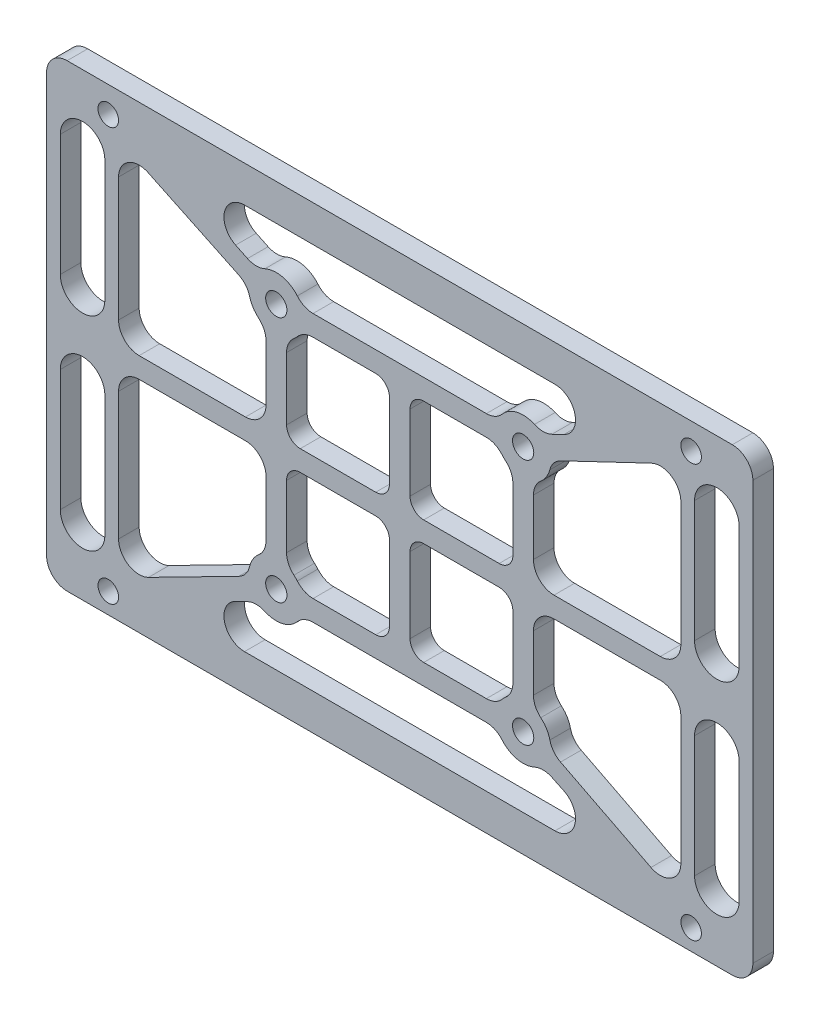
SolidWorks part; units mm, degrees
material "Thornel Mat VMA"
ref_plane "前视基准面" through (0, 0, 0) normal (0, 0, 1) x (1, 0, 0)
ref_plane "上视基准面" through (0, 0, 0) normal (0, 1, 0) x (1, 0, 0)
ref_plane "右视基准面" through (0, 0, 0) normal (1, 0, 0) x (0, 0, -1)
sketch "草图1" plane through (0, 0, 0) normal (0, 0, 1) x (1, 0, 0)
  line L1 (51.5, -33.5) -> (-51.5, -33.5)
  line L2 (51.5, -33.5) -> (51.5, 33.5)
  line L3 (51.5, 33.5) -> (-51.5, 33.5)
  line L4 (-51.5, -33.5) -> (-51.5, 33.5)
  line L5 (51.5, -33.5) -> (-51.5, 33.5) construction
  line L6 (51.5, 33.5) -> (-51.5, -33.5) construction
  point P0 (0, 0)
  dimension "D1" = 67
  dimension "D2" = 103
extrude "凸台-拉伸1" add sketch "草图1" along normal blind 3
sketch "草图2" plane through (0, 0, 3) normal (0, 0, 1) x (1, 0, 0)
  line L0 (0, 0) -> (-50000, 0) construction
  line L1 (0, 0) -> (0, 50000) construction
  circle A0 centre (-18, 18) radius 1.55
  circle A1 centre (18, 18) radius 1.55
  circle A2 centre (18, -18) radius 1.55
  circle A3 centre (-18, -18) radius 1.55
  circle A4 centre (42.5, 29.7) radius 1.5 construction
  circle A5 centre (42.5, -30.5) radius 1.5 construction
  circle A6 centre (-42.5, -30.5) radius 1.5 construction
  circle A7 centre (-42.5, 29.7) radius 1.5 construction
  circle A8 centre (42.5, 29.7) radius 1.5
  circle A9 centre (42.5, -30.5) radius 1.5
  circle A10 centre (-42.5, -30.5) radius 1.5
  circle A11 centre (-42.5, 29.7) radius 1.5
  dimension "D1" = 3.1
  dimension "D2" = 36
  dimension "D3" = 36
extrude "切除-拉伸1" cut sketch "草图2" against normal blind 10
sketch "草图4" plane through (0, 0, 3) normal (0, 0, 1) x (1, 0, 0)
  line L0 (-42.5, 29.7) -> (-42.5, -30.5) construction
  line L1 (-42.5, -30.5) -> (-18, -18) construction
  line L2 (-18, -18) -> (18, -18) construction
  line L3 (18, -18) -> (42.5, -30.5) construction
  line L4 (42.5, -30.5) -> (42.5, 29.7) construction
  line L5 (42.5, 29.7) -> (18, 18) construction
  line L6 (18, 18) -> (-18, 18) construction
  line L7 (-18, 18) -> (-42.5, 29.7) construction
  line L8 (-18, 18) -> (-18, -18) construction
  line L9 (18, 18) -> (18, -18) construction
  line L10 (-42.5, 29.7) -> (42.5, 29.7) construction
  line L11 (35.8782, 28.2) -> (17.6602, 19.5)
  line L12 (17.6602, 19.5) -> (-17.6602, 19.5)
  line L13 (-17.6602, 19.5) -> (-35.8782, 28.2)
  line L14 (-35.8782, 28.2) -> (35.8782, 28.2)
  line L15 (-19.5, 17.0541) -> (-41, 27.3214)
  line L16 (-41, 27.3214) -> (-41, -28.0507)
  line L17 (-41, -28.0507) -> (-19.5, -17.0814)
  line L18 (-19.5, 17.0541) -> (-19.5, -17.0814)
  line L19 (0, 0) -> (0, 50000) construction
  line L20 (0, 0) -> (-50000, 0) construction
  line L21 (41, -28.0507) -> (19.5, -17.0814)
  line L22 (19.5, 17.0541) -> (19.5, -17.0814)
  line L23 (19.5, 17.0541) -> (41, 27.3214)
  line L24 (41, 27.3214) -> (41, -28.0507)
  line L25 (-35.8782, -28.2) -> (35.8782, -28.2)
  line L26 (-17.6602, -19.5) -> (-35.8782, -28.2)
  line L27 (17.6602, -19.5) -> (-17.6602, -19.5)
  line L28 (35.8782, -28.2) -> (17.6602, -19.5)
  line L29 (-16.5, 16.5) -> (-16.5, -16.5)
  line L30 (-16.5, -16.5) -> (16.5, -16.5)
  line L31 (16.5, 16.5) -> (16.5, -16.5)
  line L32 (16.5, 16.5) -> (-16.5, 16.5)
  circle A0 centre (-18, 18) radius 4
  circle A1 centre (18, 18) radius 4
  circle A2 centre (-18, -18) radius 4
  circle A3 centre (18, -18) radius 4
  dimension "D4" = 8
  dimension "D1" = 1.5
  dimension "D2" = 1.5
  dimension "D3" = 1.5
extrude "切除-拉伸2" cut sketch "草图4" against normal blind 10 contours A2 L18 A0 L15 L16 L17 | A1 L11 L14 L13 A0 L12 | A3 L31 A1 L32 A0 L29 A2 L30 | A3 L21 L24 L23 A1 L22 | A3 L27 A2 L26 L25 L28
fillet "圆角1" radius 3 32 edges at (14.2919, 19.5, 1.5) (-14.2919, 19.5, 1.5) (-20.6997, 20.9515, 1.5) (-35.8782, 28.2, 1.5) (35.8782, 28.2, 1.5) (20.6997, 20.9515, 1.5) (20.6997, -20.9515, 1.5) (35.8782, -28.2, 1.5) (-35.8782, -28.2, 1.5) (-20.6997, -20.9515, 1.5) (-14.2919, -19.5, 1.5) (14.2919, -19.5, 1.5) (-21.9847, -18.3491, 1.5) (-41, -28.0507, 1.5) (-41, 27.3214, 1.5) (-19.5, 14.2919, 1.5) (-19.5, -14.2919, 1.5) (19.5, -14.2919, 1.5) (19.5, 14.2919, 1.5) (21.9925, 18.2444, 1.5) (41, 27.3214, 1.5) (41, -28.0507, 1.5) (21.9847, -18.3491, 1.5) (14.2919, -16.5, 1.5) (-14.2919, -16.5, 1.5) (-16.5, -14.2919, 1.5) (-16.5, 14.2919, 1.5) (-14.2919, 16.5, 1.5) (14.2919, 16.5, 1.5) (16.5, 14.2919, 1.5) (16.5, -14.2919, 1.5) (-21.9925, 18.2444, 1.5)
sketch "草图5" plane through (0, 0, 3) normal (0, 0, 1) x (1, 0, 0)
  line L0 (0, 0) -> (-50000, 0) construction
  line L1 (-43.1119, 1.5) -> (-43.1119, -1.5)
  line L2 (-43.1119, -1.5) -> (-17.8407, -1.5)
  line L3 (-17.8407, -1.5) -> (-17.8407, 1.5)
  line L4 (-17.8407, 1.5) -> (-43.1119, 1.5)
  line L5 (0, 0) -> (0, 50000) construction
  line L6 (17.8407, 1.5) -> (43.1119, 1.5)
  line L7 (17.8407, -1.5) -> (17.8407, 1.5)
  line L8 (43.1119, -1.5) -> (17.8407, -1.5)
  line L9 (43.1119, 1.5) -> (43.1119, -1.5)
  dimension "D1" = 1.5
  dimension "D2" = 1.5
extrude "凸台-拉伸2" add sketch "草图5" against normal up to surface (3 mm away) up to face at (0, 0, 0)
fillet "圆角2" radius 3 12 edges at (-19.5, -1.5, 1.5) (-41, -1.5, 1.5) (-41, 1.5, 1.5) (-19.5, 1.5, 1.5) (41, -1.5, 1.5) (19.5, -1.5, 1.5) (19.5, 1.5, 1.5) (41, 1.5, 1.5) (51.5, 33.5, 1.5) (51.5, -33.5, 1.5) (-51.5, -33.5, 1.5) (-51.5, 33.5, 1.5)
sketch "草图6" plane through (0, 0, 3) normal (0, 0, 1) x (1, 0, 0)
  line L0 (0, 0) -> (-50000, 0) construction
  line L1 (0, 0) -> (0, 50000) construction
  line L2 (-46.25, 23.7) -> (-46.25, 6) construction
  line L3 (-43, 23.7) -> (-43, 6)
  line L4 (-49.5, 23.7) -> (-49.5, 6)
  line L5 (-51.5, 30.5) -> (-51.5, -30.5) construction
  line L6 (-41, 22.5642) -> (-41, 4.5) construction
  line L7 (46.25, 23.7) -> (46.25, 6) construction
  line L8 (43, 23.7) -> (43, 6)
  line L9 (49.5, 23.7) -> (49.5, 6)
  line L10 (46.25, -23.7) -> (46.25, -6) construction
  line L11 (43, -23.7) -> (43, -6)
  line L12 (49.5, -23.7) -> (49.5, -6)
  line L13 (-46.25, -23.7) -> (-46.25, -6) construction
  line L14 (-43, -23.7) -> (-43, -6)
  line L15 (-49.5, -23.7) -> (-49.5, -6)
  arc A0 (-43, 23.7) -> (-49.5, 23.7) centre (-46.25, 23.7) ccw
  arc A1 (-49.5, 6) -> (-43, 6) centre (-46.25, 6) ccw
  circle A2 centre (-42.5, 29.7) radius 1.5 construction
  arc A3 (43, 23.7) -> (49.5, 23.7) centre (46.25, 23.7) cw
  arc A4 (49.5, 6) -> (43, 6) centre (46.25, 6) cw
  arc A5 (43, -23.7) -> (49.5, -23.7) centre (46.25, -23.7) ccw
  arc A6 (49.5, -6) -> (43, -6) centre (46.25, -6) ccw
  arc A7 (-43, -23.7) -> (-49.5, -23.7) centre (-46.25, -23.7) cw
  arc A8 (-49.5, -6) -> (-43, -6) centre (-46.25, -6) cw
  point P7 (-46.25, 14.85)
  point P20 (46.25, 14.85)
  point P27 (46.25, -14.85)
  point P34 (-46.25, -14.85)
  dimension "D1" = 2
  dimension "D2" = 2
  dimension "D3" = 6
  dimension "D4" = 6
extrude "切除-拉伸3" cut sketch "草图6" against normal blind 10
sketch "草图7" plane through (0, 0, 3) normal (0, 0, 1) x (1, 0, 0)
  line L0 (-16.5, 0) -> (16.5, 0) construction
  line L1 (-16.5, 12.6381) -> (-16.5, -12.6381) construction
  line L2 (16.5, 12.6381) -> (16.5, -12.6381) construction
  line L3 (0, 16.5) -> (0, -16.5) construction
  line L4 (12.6381, 16.5) -> (-12.6381, 16.5) construction
  line L5 (-12.6381, -16.5) -> (12.6381, -16.5) construction
  line L6 (-1.5, 16.5) -> (-1.5, -16.5)
  line L7 (-16.5, -1.5) -> (16.5, -1.5)
  line L8 (1.5, 16.5) -> (1.5, -16.5)
  line L9 (-16.5, 1.5) -> (16.5, 1.5)
  line L10 (-16.5, 1.5) -> (-16.5, -1.5)
  line L11 (-1.5, -16.5) -> (1.5, -16.5)
  line L12 (16.5, 1.5) -> (16.5, -1.5)
  line L13 (1.5, 16.5) -> (-1.5, 16.5)
  dimension "D1" = 1.5
  dimension "D2" = 1.5
extrude "凸台-拉伸3" add sketch "草图7" against normal up to surface (3 mm away) contours L8 L13 L6 L9 | L9 L10 L7 L6 | L9 L6 L7 L8 | L12 L9 L8 L7 | L6 L11 L8 L7 up to face at (-46.25, -14.85, 0)
fillet "圆角3" radius 2 12 edges at (1.5, -16.5, 1.5) (1.5, -1.5, 1.5) (16.5, -1.5, 1.5) (16.5, 1.5, 1.5) (1.5, 1.5, 1.5) (-1.5, 16.5, 1.5) (-1.5, 1.5, 1.5) (-16.5, 1.5, 1.5) (-16.5, -1.5, 1.5) (-1.5, -1.5, 1.5) (-1.5, -16.5, 1.5) (1.5, 16.5, 1.5)
